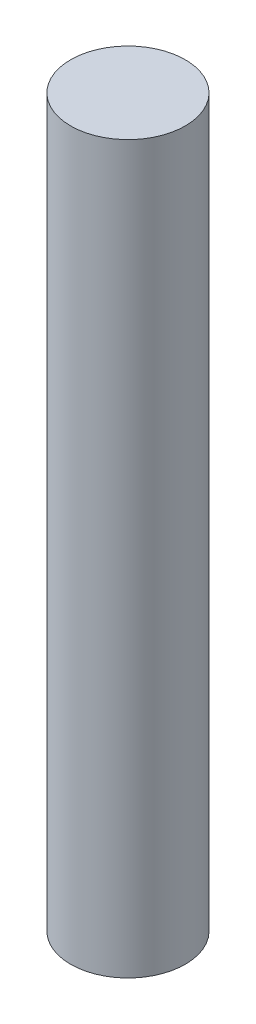
SolidWorks part; units mm, degrees
ref_plane "Front Plane" through (0, 0, 0) normal (0, 0, 1) x (1, 0, 0)
ref_plane "Top Plane" through (0, 0, 0) normal (0, 1, 0) x (1, 0, 0)
ref_plane "Right Plane" through (0, 0, 0) normal (1, 0, 0) x (0, 0, -1)
sketch "Sketch1" plane through (0, 0, 0) normal (0, 1, 0) x (1, 0, 0)
  circle A0 centre (0, 0) radius 39.49
  dimension "D1" = 78.98
extrude "Boss-Extrude1" add sketch "Sketch1" along normal blind 500
